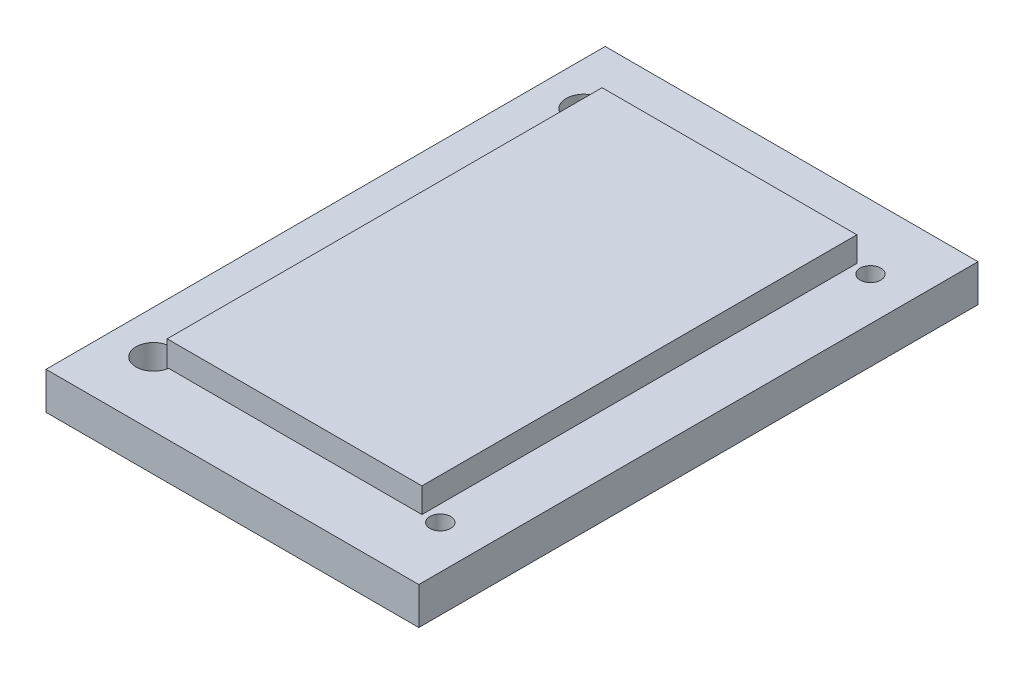
SolidWorks part; units mm, degrees
ref_plane "前视基准面" through (0, 0, 0) normal (0, 0, 1) x (1, 0, 0)
ref_plane "上视基准面" through (0, 0, 0) normal (0, 1, 0) x (1, 0, 0)
ref_plane "右视基准面" through (0, 0, 0) normal (1, 0, 0) x (0, 0, -1)
other "Configuration Table"
sketch "01_Base_Profile" plane through (0, 0, 0) normal (0, 1, 0) x (1, 0, 0)
  line L1 (-60, -90) -> (60, -90)
  line L2 (-60, -90) -> (-60, 90)
  line L3 (-60, 90) -> (60, 90)
  line L4 (60, -90) -> (60, 90)
  line L5 (-60, -90) -> (60, 90) construction
  line L6 (-60, 90) -> (60, -90) construction
  line L7 (-9, -62.5) -> (9, -62.5)
  line L8 (-9, -62.5) -> (-9, 62.5)
  line L9 (-9, 62.5) -> (9, 62.5)
  line L10 (9, -62.5) -> (9, 62.5)
  line L11 (-9, -62.5) -> (9, 62.5) construction
  line L12 (-9, 62.5) -> (9, -62.5) construction
  circle A0 centre (-46.1538, -69.2308) radius 5.6538
  circle A1 centre (46.1538, -69.2308) radius 3.3462
  circle A2 centre (-46.1538, 69.2308) radius 5.6538
  circle A3 centre (46.1538, 69.2308) radius 3.3462
  point P0 (0, 0)
  point P14 (0, 0)
extrude "01_Base_Extrude" add sketch "01_Base_Profile" along normal blind 12
sketch "02_Boss_Profile" plane through (0, 0, 0) normal (0, 1, 0) x (1, 0, 0)
  line L1 (-41, -70) -> (41, -70)
  line L2 (-41, -70) -> (-41, 70)
  line L3 (-41, 70) -> (41, 70)
  line L4 (41, -70) -> (41, 70)
  line L5 (-41, -70) -> (41, 70) construction
  line L6 (-41, 70) -> (41, -70) construction
  point P0 (0, 0)
extrude "02_Reinforcement_Boss" add sketch "02_Boss_Profile" along normal blind 20
